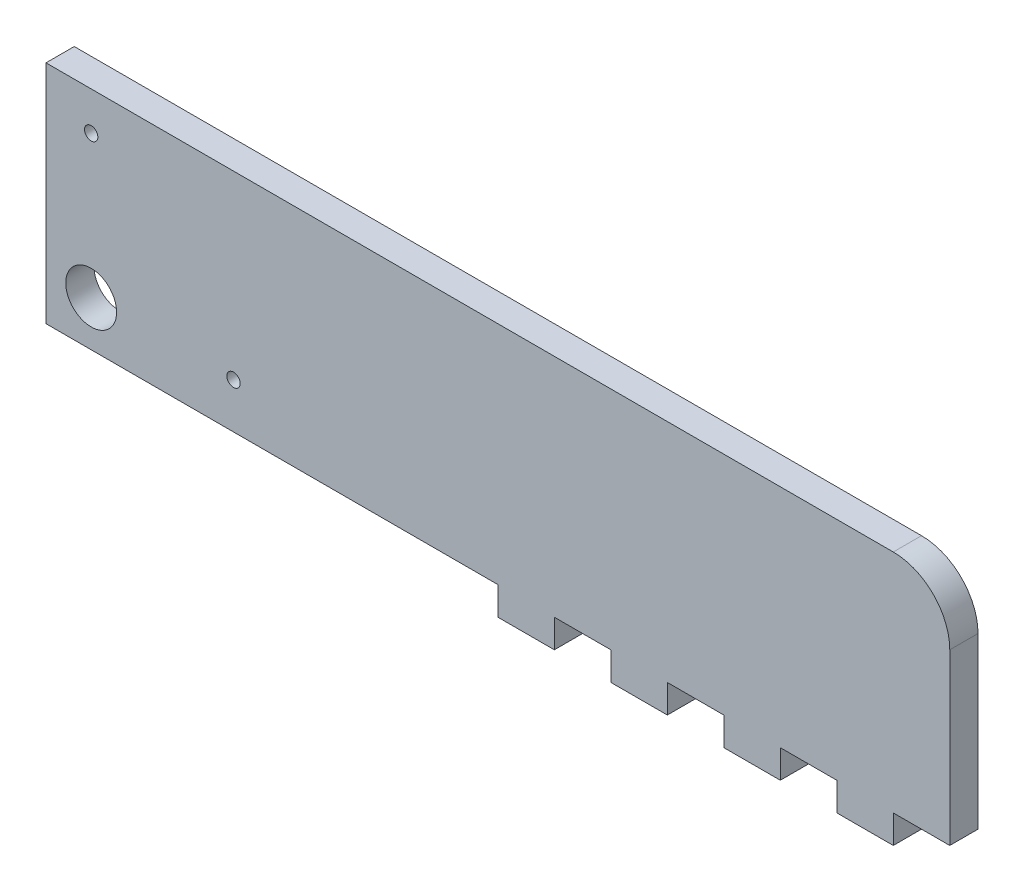
SolidWorks part; units mm, degrees
material "Acrylic (Medium-high impact)"
ref_plane "Front Plane" through (0, 0, 0) normal (0, 0, 1) x (1, 0, 0)
ref_plane "Top Plane" through (0, 0, 0) normal (0, 1, 0) x (1, 0, 0)
ref_plane "Right Plane" through (0, 0, 0) normal (1, 0, 0) x (0, 0, -1)
sketch "Sketch1" plane through (0, 0, 0) normal (0, 0, 1) x (1, 0, 0)
  line L0 (95.25, 0) -> (95.25, -3.175)
  line L1 (0, 0) -> (44.45, 0)
  line L2 (0, 0) -> (0, 25.4)
  line L3 (0, 25.4) -> (101.6, 25.4)
  line L4 (101.6, 0) -> (101.6, 25.4)
  line L5 (95.25, -3.175) -> (88.9, -3.175)
  line L6 (88.9, -3.175) -> (88.9, 0)
  line L7 (95.25, 0) -> (101.6, 0)
  line L24 (44.45, 0) -> (50.8, 0)
  line L25 (57.15, 0) -> (63.5, 0)
  line L26 (69.85, 0) -> (76.2, 0)
  line L27 (82.55, 0) -> (88.9, 0)
  line L28 (82.55, 0) -> (82.55, -3.175)
  line L29 (82.55, -3.175) -> (76.2, -3.175)
  line L30 (76.2, -3.175) -> (76.2, 0)
  line L31 (69.85, 0) -> (69.85, -3.175)
  line L32 (69.85, -3.175) -> (63.5, -3.175)
  line L33 (63.5, -3.175) -> (63.5, 0)
  line L34 (57.15, 0) -> (57.15, -3.175)
  line L35 (57.15, -3.175) -> (50.8, -3.175)
  line L36 (50.8, -3.175) -> (50.8, 0)
  line L37 (44.45, 0) -> (44.45, -3.175) [skipped]
  line L38 (44.45, -3.175) -> (38.1, -3.175) [skipped]
  line L39 (38.1, -3.175) -> (38.1, 0) [skipped]
  line L40 (31.75, 0) -> (31.75, -3.175) [skipped]
  line L41 (31.75, -3.175) -> (25.4, -3.175) [skipped]
  line L42 (25.4, -3.175) -> (25.4, 0) [skipped]
  circle A0 centre (5.08, 5.08) radius 2.8575
  circle A1 centre (5.08, 21.08) radius 0.75
  circle A2 centre (21.08, 5.08) radius 0.75
  dimension "D9" = 5.08
  dimension "D8" = 5.715
  dimension "D11" = 1.5
  dimension "D1" = 25.4
  dimension "D2" = 101.6
  dimension "D3" = 3.175
  dimension "D4" = 6.35
  dimension "D5" = 6.35
  dimension "D7" = 6.35
  dimension "D10" = 5.08
  dimension "D12" = 16
  dimension "D13" = 16
  dimension "D14" = 6.35
  dimension "D6" = 4
extrude "Boss-Extrude1" add sketch "Sketch1" along normal blind 3.175
fillet "Fillet1" radius 6.35 1 edges at (101.6, 25.4, 1.5875)
